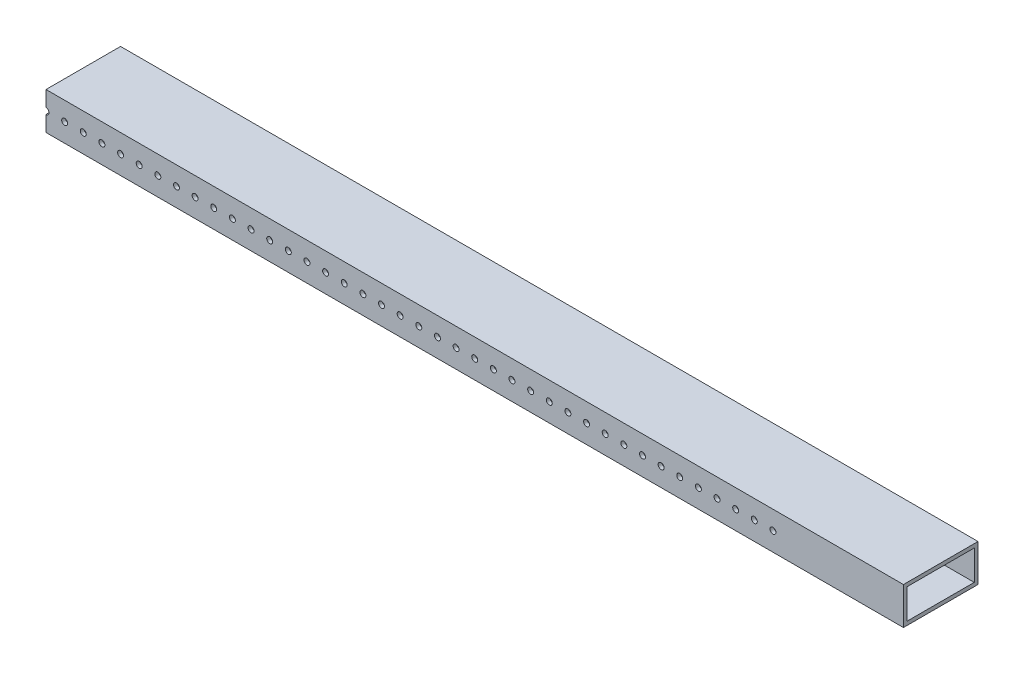
SolidWorks part; units mm, degrees
ref_plane "Front Plane" through (0, 0, 0) normal (0, 0, 1) x (1, 0, 0)
ref_plane "Top Plane" through (0, 0, 0) normal (0, 1, 0) x (1, 0, 0)
ref_plane "Right Plane" through (0, 0, 0) normal (1, 0, 0) x (0, 0, -1)
sketch "Sketch1" plane through (0, 0, 0) normal (1, 0, 0) x (0, 0, -1)
  line L0 (-22.86, 10.16) -> (22.86, 10.16)
  line L1 (-25.4, -12.7) -> (25.4, -12.7)
  line L2 (-25.4, -12.7) -> (-25.4, 12.7)
  line L3 (-25.4, 12.7) -> (25.4, 12.7)
  line L4 (25.4, -12.7) -> (25.4, 12.7)
  line L5 (-25.4, -12.7) -> (25.4, 12.7) construction
  line L6 (-25.4, 12.7) -> (25.4, -12.7) construction
  line L7 (22.86, -10.16) -> (22.86, 10.16)
  line L8 (-22.86, -10.16) -> (22.86, -10.16)
  line L9 (-22.86, -10.16) -> (-22.86, 10.16)
  point P0 (0, 0)
  dimension "D1" = 50.8
  dimension "D2" = 25.4
  dimension "D3" = 2.54
extrude "Boss-Extrude1" add sketch "Sketch1" along normal mid plane 584.2
sketch "Sketch2" plane through (0, 0, 25.4) normal (0, 0, 1) x (1, 0, 0)
  line L0 (-292.1, 12.7) -> (-292.1, -12.7) construction
  circle A0 centre (-292.1, 0) radius 2.032
  circle A1 centre (-279.4, 0) radius 2.032
  circle A2 centre (-266.7, 0) radius 2.032
  circle A3 centre (-254, 0) radius 2.032
  circle A4 centre (-241.3, 0) radius 2.032
  circle A5 centre (-228.6, 0) radius 2.032
  circle A6 centre (-215.9, 0) radius 2.032
  circle A7 centre (-203.2, 0) radius 2.032
  circle A8 centre (-190.5, 0) radius 2.032
  circle A9 centre (-177.8, 0) radius 2.032
  circle A10 centre (-165.1, 0) radius 2.032
  circle A11 centre (-152.4, 0) radius 2.032
  circle A12 centre (-139.7, 0) radius 2.032
  circle A13 centre (-127, 0) radius 2.032
  circle A14 centre (-114.3, 0) radius 2.032
  circle A15 centre (-101.6, 0) radius 2.032
  circle A16 centre (-88.9, 0) radius 2.032
  circle A17 centre (-76.2, 0) radius 2.032
  circle A18 centre (-63.5, 0) radius 2.032
  circle A19 centre (-50.8, 0) radius 2.032
  circle A20 centre (-38.1, 0) radius 2.032
  circle A21 centre (-25.4, 0) radius 2.032
  circle A22 centre (-12.7, 0) radius 2.032
  circle A23 centre (0, 0) radius 2.032
  circle A24 centre (12.7, 0) radius 2.032
  circle A25 centre (25.4, 0) radius 2.032
  circle A26 centre (38.1, 0) radius 2.032
  circle A27 centre (50.8, 0) radius 2.032
  circle A28 centre (63.5, 0) radius 2.032
  circle A29 centre (76.2, 0) radius 2.032
  circle A30 centre (88.9, 0) radius 2.032
  circle A31 centre (101.6, 0) radius 2.032
  circle A32 centre (114.3, 0) radius 2.032
  circle A33 centre (127, 0) radius 2.032
  circle A34 centre (139.7, 0) radius 2.032
  circle A35 centre (152.4, 0) radius 2.032
  circle A36 centre (165.1, 0) radius 2.032
  circle A37 centre (177.8, 0) radius 2.032
  circle A38 centre (190.5, 0) radius 2.032
  circle A39 centre (203.2, 0) radius 2.032
  dimension "D1" = 4.064
  dimension "D2" = 40
extrude "Cut-Extrude1" cut sketch "Sketch2" against normal through all
